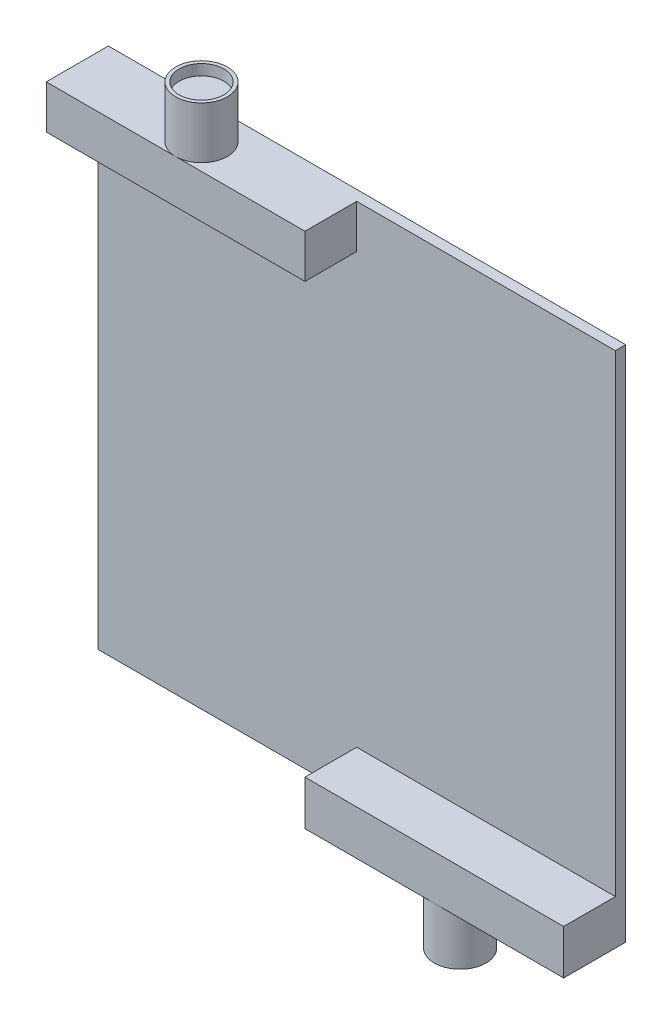
SolidWorks part; units mm, degrees
ref_plane "Front Plane" through (0, 0, 0) normal (0, 0, 1) x (1, 0, 0)
ref_plane "Top Plane" through (0, 0, 0) normal (0, 1, 0) x (1, 0, 0)
ref_plane "Right Plane" through (0, 0, 0) normal (1, 0, 0) x (0, 0, -1)
sketch "Sketch1" plane through (0, 0, 0) normal (0, 0, 1) x (1, 0, 0)
  line L1 (-75, -75) -> (75, -75)
  line L2 (-75, -75) -> (-75, 75)
  line L3 (-75, 75) -> (75, 75)
  line L4 (75, -75) -> (75, 75)
  line L5 (-75, -75) -> (75, 75) construction
  line L6 (-75, 75) -> (75, -75) construction
  point P0 (0, 0)
  dimension "D1" = 150
  dimension "D2" = 150
extrude "Boss-Extrude1" add sketch "Sketch1" along normal blind 3
sketch "Sketch2" plane through (0, -75, 0) normal (0, -1, 0) x (1, 0, 0)
  line L0 (-75, 3) -> (75, 3) construction
  line L1 (37.5, 10.5) -> (37.5, 3) construction
  line L2 (75, 3) -> (75, 0) construction
  circle A0 centre (37.5, 10.5) radius 7.5
  spline S0 degree 2 poles (75, 3) (108.4088, 3.7051) (45, 10.5) knots 0 0 0 1 1 1
  spline S1 degree 2 poles (0, 3) (-33.4088, 3.7051) (30, 10.5) knots 0 0 0 1 1 1
  dimension "D1" = 15
  dimension "D2" = 37.5
sketch "Sketch4" plane through (0, 75, 0) normal (0, 1, 0) x (1, 0, 0)
  line L0 (75, -3) -> (-75, -3) construction
  line L1 (-37.5, -10.5) -> (-37.5, -3) construction
  line L2 (-75, -3) -> (-75, 0) construction
  circle A0 centre (-37.5, -10.5) radius 7.5
  dimension "D1" = 15
  dimension "D2" = 37.5
extrude "Boss-Extrude2" add sketch "Sketch2" along normal blind 15 separate body contours A0
extrude "Boss-Extrude3" add sketch "Sketch4" along normal blind 15 separate body
sketch "Sketch8" plane through (0, -90, 0) normal (0, -1, 0) x (1, 0, 0)
  circle A0 centre (37.5, 10.5) radius 6.5
  dimension "D1" = 13
sketch "Sketch9" plane through (0, 90, 0) normal (0, 1, 0) x (1, 0, 0)
  circle A0 centre (-37.5, -10.5) radius 6.5
  dimension "D1" = 13
extrude "Cut-Extrude1" cut sketch "Sketch8" against normal blind 3.1
extrude "Cut-Extrude2" cut sketch "Sketch9" against normal blind 3.1
sketch "Sketch10" plane through (0, 0, 3) normal (0, 0, 1) x (1, 0, 0)
  line L0 (0, 75) -> (-75, 75)
  line L1 (0, 75) -> (0, 62.4039)
  line L2 (-75, 75) -> (-75, 62.4039)
  line L3 (0, 62.4039) -> (-75, 62.4039)
  line L4 (75, 75) -> (-75, 75) construction
  line L5 (75, -75) -> (0, -75)
  line L6 (75, -75) -> (75, -62.0595)
  line L7 (0, -75) -> (0, -62.0595)
  line L8 (75, -62.0595) -> (0, -62.0595)
  line L9 (-75, -75) -> (75, -75) construction
extrude "Boss-Extrude4" add sketch "Sketch10" along normal blind 15
